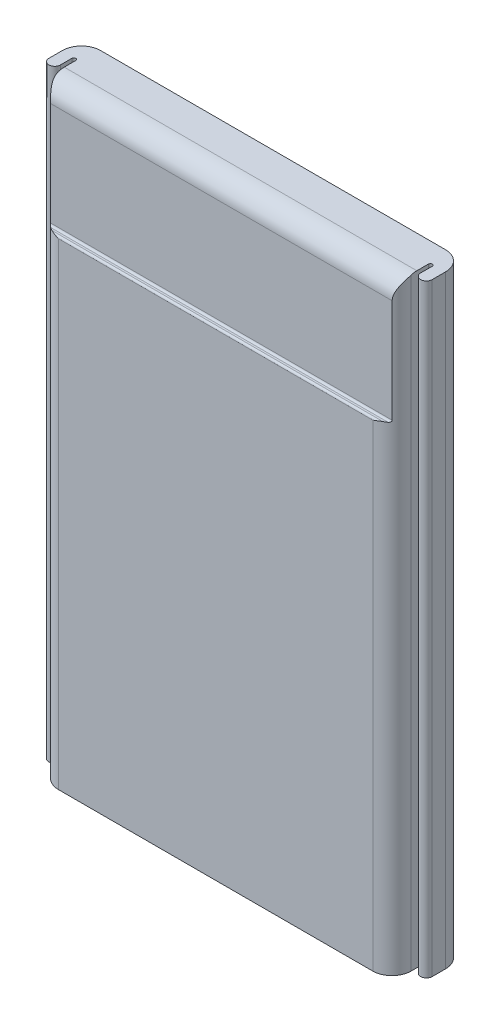
SolidWorks part; units mm, degrees
ref_plane "Front" through (0, 0, 0) normal (0, 0, 1) x (1, 0, 0)
ref_plane "Top" through (0, 0, 0) normal (0, 1, 0) x (1, 0, 0)
ref_plane "Right" through (0, 0, 0) normal (1, 0, 0) x (0, 0, -1)
sketch "Эскиз1" plane through (0, 0, 0) normal (0, 1, 0) x (1, 0, 0)
  line L0 (-9, 0) -> (9, 0)
  line L1 (-8.2, -3) -> (8.2, -3)
  line L2 (-10, -1) -> (-10, -1.7)
  line L3 (10, -1) -> (10, -1.7)
  line L4 (-9.2, -2) -> (-9.2, -1.1)
  line L5 (9.2, -1.1) -> (9.2, -2)
  line L6 (9.4, -1.7) -> (9.4, -1.1)
  line L7 (-9.4, -1.7) -> (-9.4, -1.1)
  arc A0 (-9, 0) -> (-10, -1) centre (-9, -1) ccw
  arc A1 (9, 0) -> (10, -1) centre (9, -1) cw
  arc A2 (-9.2, -2) -> (-8.2, -3) centre (-8.2, -2) ccw
  arc A3 (9.2, -2) -> (8.2, -3) centre (8.2, -2) cw
  arc A4 (10, -1.7) -> (9.4, -1.7) centre (9.7, -1.7) cw
  arc A5 (9.2, -1.1) -> (9.4, -1.1) centre (9.3, -1.1) cw
  arc A6 (-10, -1.7) -> (-9.4, -1.7) centre (-9.7, -1.7) ccw
  arc A7 (-9.2, -1.1) -> (-9.4, -1.1) centre (-9.3, -1.1) ccw
  point P20 (9.3, -1)
  point P21 (9.7, -2)
  point P27 (-9.3, -1)
  point P28 (-9.7, -2)
  dimension "D1" = 20
  dimension "D3" = 1
  dimension "D4" = 1
  dimension "D5" = 0.3
  dimension "D6" = 0.1
  dimension "D2" = 3
extrude "Бобышка-Вытянуть1" add sketch "Эскиз1" along normal mid plane 31.5
sketch "Эскиз2" plane through (0, 0, 0) normal (1, 0, 0) x (0, 0, -1)
  line L0 (-2.7, 14.75) -> (-2.7, 9.35)
  line L1 (-2.8, 9.25) -> (-2.9, 9.25)
  line L2 (-3, 15.75) -> (-3, 9.15)
  line L3 (-3, 15.75) -> (-3, -15.75) construction
  line L6 (-3, 15.75) -> (-1.7, 15.75)
  line L7 (0, 15.75) -> (-1, 15.75) construction
  arc A0 (-2.7, 9.35) -> (-2.8, 9.25) centre (-2.8, 9.35) cw
  arc A1 (-2.9, 9.25) -> (-3, 9.15) centre (-2.9, 9.15) ccw
  arc A2 (-1.7, 15.75) -> (-2.7, 14.75) centre (-1.7, 14.75) ccw
  dimension "D1" = 0.1
  dimension "D4" = 1
  dimension "D2" = 2.7
  dimension "D3" = 6.5
extrude "Вырез-Вытянуть1" cut sketch "Эскиз2" against normal up to next and the other way up to next
